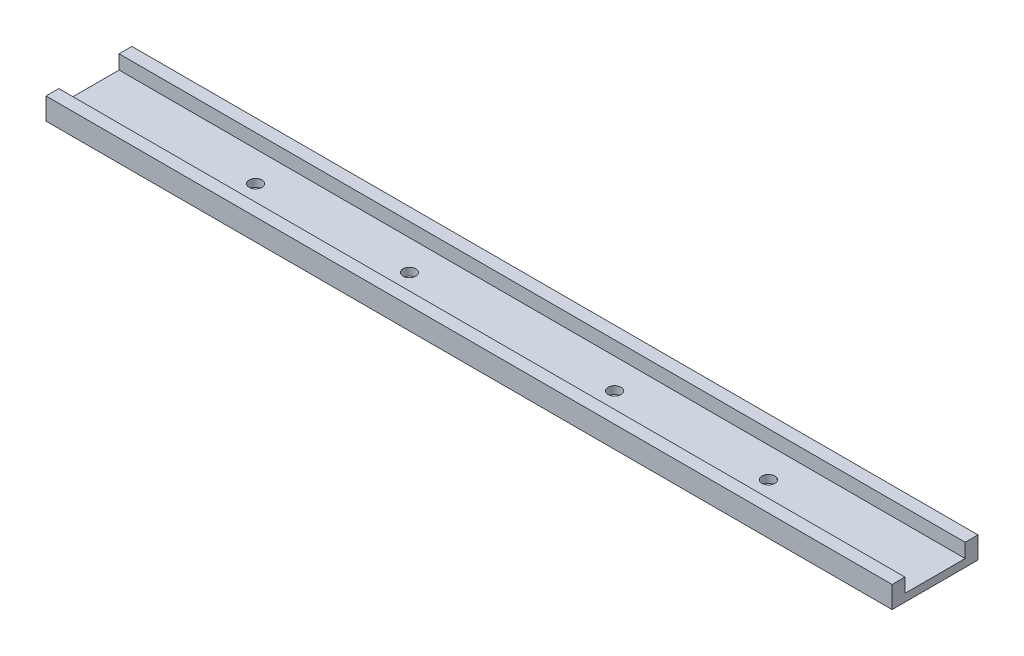
SolidWorks part; units mm, degrees
material "Обычная углеродистая сталь"
ref_plane "Спереди" through (0, 0, 0) normal (0, 0, 1) x (1, 0, 0)
ref_plane "Сверху" through (0, 0, 0) normal (0, 1, 0) x (1, 0, 0)
ref_plane "Справа" through (0, 0, 0) normal (1, 0, 0) x (0, 0, -1)
ref_plane "Плоскость4" through (0, 8.5, 0) normal (0, 1, 0) x (1, 0, 0)
sketch "Эскиз1" plane through (0, 8.5, 0) normal (0, 1, 0) x (1, 0, 0)
  line L0 (330, 0) -> (0, 0)
  line L1 (0, 0) -> (0, -33.5)
  line L2 (0, -33.5) -> (330, -33.5)
  line L3 (330, -33.5) -> (330, 0)
extrude "Бобышка-Вытянуть1" add sketch "Эскиз1" against normal blind 8.5
sketch "Эскиз2" plane through (330, 0, 0) normal (1, 0, 0) x (0, 0, -1)
  line L0 (-28.5, 8.5) -> (-28.5, 3)
  line L1 (-28.5, 3) -> (-5, 3)
  line L2 (-5, 3) -> (-5, 8.5)
  line L3 (-5, 8.5) -> (-28.5, 8.5)
extrude "Вырез-Вытянуть1" cut sketch "Эскиз2" against normal through all
hole_wizard "Диаметр отверстия Ø5.0 (5)1" positions "Эскиз4" profile "Эскиз3" hole size "Ø5.0" standard "Ansi Metric"
sketch "Эскиз4" plane through (0, 3, 0) normal (0, 1, 0) x (1, 0, 0)
  point P0 (65, -16.75)
  point P1 (125, -16.75)
  point P2 (265, -16.75)
  point P3 (205, -16.75)
sketch "Эскиз3" plane through (65, 3, 16.75) normal (1, 0, 0) x (0, 0, 1)
  line L0 (0, 0) -> (0, 3)
  line L1 (0, 3) -> (2.5, 3)
  line L2 (2.5, 3) -> (2.5, 0)
  line L5 (2.5, 0) -> (0, 0)
  line L11 (0, -6.35) -> (0, 107.95) construction
  dimension "Диаметр сквозного отверстия" = 5
  dimension "Глубина сквозного отверстия" = 3
